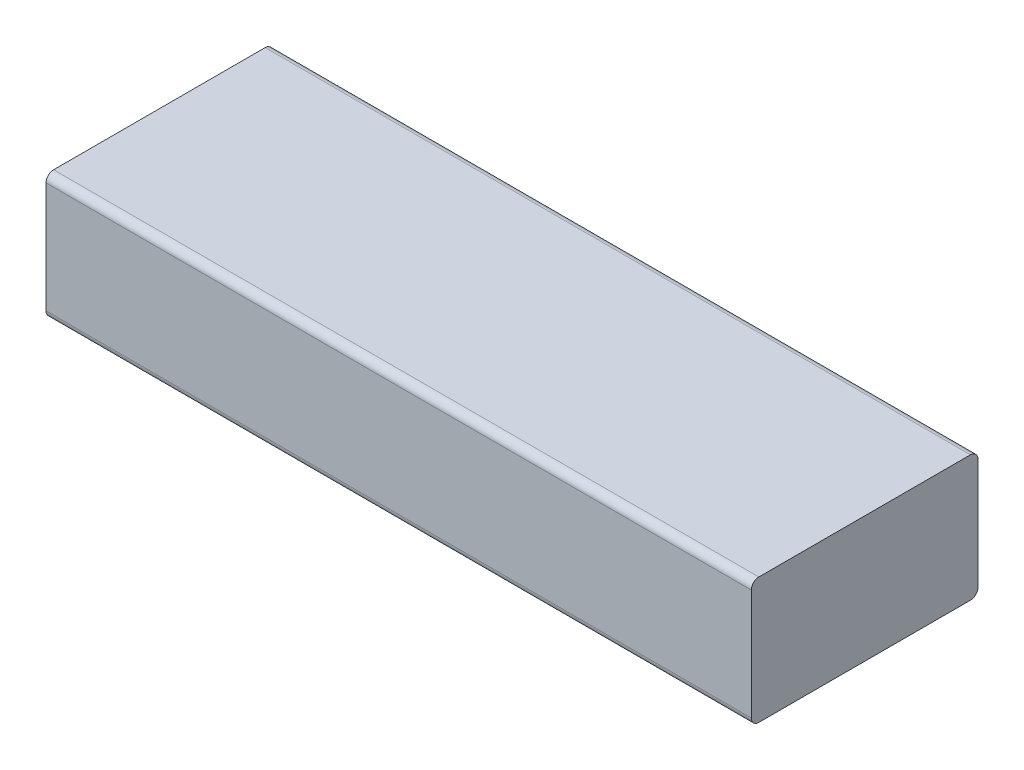
SolidWorks part; units mm, degrees
ref_plane "Plan de face" through (0, 0, 0) normal (0, 0, 1) x (1, 0, 0)
ref_plane "Plan de dessus" through (0, 0, 0) normal (0, 1, 0) x (1, 0, 0)
ref_plane "Plan de droite" through (0, 0, 0) normal (1, 0, 0) x (0, 0, -1)
sketch "Esquisse2" plane through (0, 0, 0) normal (0, 1, 0) x (1, 0, 0)
  line L0 (0, 0) -> (70, 0)
  line L1 (70, 0) -> (70, 45)
  line L2 (70, 45) -> (-70, 45)
  line L3 (-70, 45) -> (-70, 0)
  line L4 (-70, 0) -> (0, 0)
extrude "Boss.-Extru.1" add sketch "Esquisse2" along normal blind 25
fillet "Congé1" radius 1.5 4 edges at (0, 0, -45) (0, 25, -45) (0, 0, 0) (0, 25, 0)
sketch "Esquisse4" plane through (0, 25, 0) normal (0, 1, 0) x (1, 0, 0)
